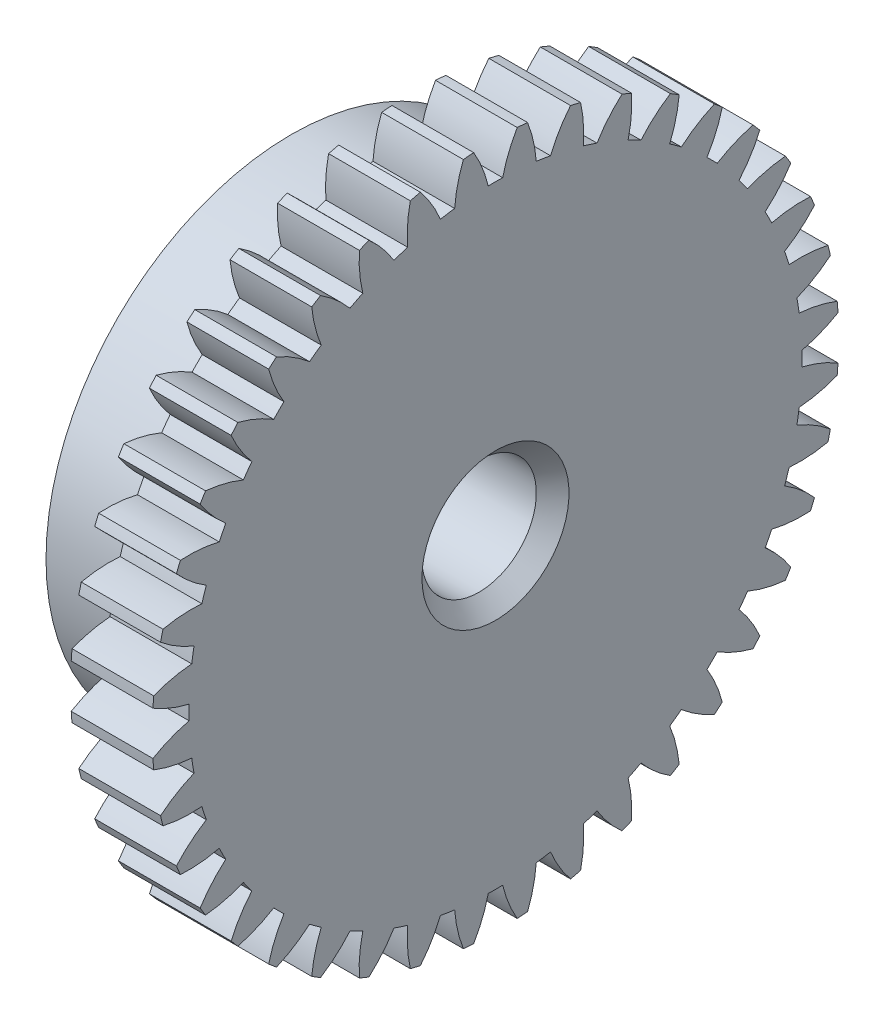
SolidWorks part; units mm, degrees
ref_plane "Plane1" through (0, 0, 0) normal (0, 0, 1) x (1, 0, 0)
ref_plane "Plane2" through (0, 0, 0) normal (0, 1, 0) x (1, 0, 0)
ref_plane "Plane3" through (0, 0, 0) normal (1, 0, 0) x (0, 0, -1)
sketch "HoldingSke" plane through (0, 0, 0) normal (0, 1, 0) x (1, 0, 0)
  line L0 (0, 0) -> (0.383, -0.3214)
  line L1 (-15, 0) -> (100, 0) construction
  line L2 (0, 0) -> (-2.1039, 2.3779)
  line L3 (0, 0) -> (-11.863, 4.5341)
  line L4 (0, 0) -> (6.6156, 5.5511)
  line L5 (0, 0) -> (-23.4238, -8.7364)
  line L6 (0, 0) -> (-8.2896, -5.593)
  line L7 (-2.1039, 2.3779) -> (3.2774, 26.7919)
  line L8 (-76.2, 54.61) -> (-73.9, 54.61)
  line L9 (-71.009, 38.7566) -> (-53.1078, 45.2721)
  line L10 (-76.2, 71.12) -> (104.1128, 71.12)
  line L11 (0, 0) -> (-10, 0)
  line L12 (-76.2, 101.6) -> (-76.133, 101.6)
  line L13 (24.9733, 27.94) -> (52.9518, 28.4284)
  line L14 (24.9733, 27.94) -> (24.9743, 27.94)
  line L15 (24.9733, 27.94) -> (100.4006, 29.5858)
  line L16 (-63.627, -2) -> (-12.827, -2)
  circle A0 centre (0, 0) radius 7
  circle A1 centre (0, 0) radius 30
  circle A2 centre (0, 0) radius 30
  circle A3 centre (0, 0) radius 7
  dimension "MHD" = 60
  dimension "Hub_dia" = 60
  dimension "Bore" = 14
  dimension "MBD" = 14
  dimension "Num_teeth" = 40
  dimension "Pitch" = 0.5
  dimension "Overall_len" = 25
  dimension "Show_teeth" = 40
  dimension "Thickness" = 10
  dimension "OAL" = 25.0001
  dimension "T_dim" = 2.3
  dimension "Ap" = 20
  dimension "H" = 19.05
  dimension "Pitch_radius" = 180.3128
  dimension "Width" = 10
  dimension "Backlash" = 0.067
  dimension "Addendum_fac" = 1
  dimension "Dedendum_fac" = 1.25
  dimension "Clearance_fac" = 0.25
  dimension "Dedendum_add" = 0.001
  dimension "Module" = 2
sketch "BasProSke" plane through (0, 0, 0) normal (0, 1, 0) x (1, 0, 0)
  line L0 (-10, 0) -> (60, 0) construction
  line L1 (0, 0) -> (0, 42)
  line L2 (0, 0) -> (10, 0)
  line L3 (10, 0) -> (10, 42)
  line L4 (10, 42) -> (0, 42)
  dimension "Thickness" = 10
  dimension "Diameter" = 84
revolve "Base-Revolve" add sketch "BasProSke" angle 360 about L0
sketch "TooCutSke" plane through (0, 0, 0) normal (1, 0, 0) x (0, 0, -1)
  line L1 (0, 0) -> (0, 107) construction
  line L2 (0, 0) -> (-1.6876, 39.9644) construction
  line L3 (0, 0) -> (-6.2726, 79.7007) construction
  line L4 (-1.6876, 39.9644) -> (-3.1363, 39.8504) construction
  arc A0 (0.8828, 37.4886) -> (-0.8828, 37.4886) centre (0, 0) ccw
  arc A1 (2.6784, 41.94) -> (-2.6784, 41.94) centre (0, 0) ccw
  circle A2 centre (0, 0) radius 40 construction
  circle A3 centre (0, 0) radius 37.5877 construction
  arc A4 (-0.8828, 37.4886) -> (-2.6784, 41.94) centre (-16.451, 33.7965) ccw
  arc A5 (2.6784, 41.94) -> (0.8828, 37.4886) centre (16.451, 33.7965) ccw
  dimension "Root_dia" = 74.998
  dimension "Overcut_dia" = 84.0508
  dimension "Pitch_dia" = 80
  dimension "Base_dia" = 75.1754
  dimension "Flank_rad" = 16
  dimension "Half_ang" = 4.5
  dimension "Half_CT" = 1.4531
extrude "ToothCut" cut sketch "TooCutSke" along normal through all
fillet "Breaks" [suppressed] radius 0.04
fillet "RootFillets" [suppressed] radius 0.501
pattern_circular "TeethCuts" count 40 every 9 about axis through (-10, 0, 0) along (1, 0, 0) of "ToothCut", "RootFillets", "Breaks"
sketch "HubNeaOneSke" plane through (0, 0, 0) normal (-1, 0, 0) x (0, 0, 1)
  circle A0 centre (0, 0) radius 30
  dimension "Diameter" = 60
extrude "HubNearOne" add sketch "HubNeaOneSke" along normal blind 15.0001
sketch "HubNeaBotSke" plane through (0, 0, 0) normal (-1, 0, 0) x (0, 0, 1)
  circle A0 centre (0, 0) radius 30
  dimension "Diameter" = 60
extrude "HubNearBoth" [suppressed] add sketch "HubNeaBotSke" along normal blind 7.5
ref_plane "FarPln" through (10, 0, 0) normal (1, 0, 0) x (0, 0, -1)
sketch "HubFarSke" plane through (10, 0, 0) normal (1, 0, 0) x (0, 0, -1)
  circle A0 centre (0, 0) radius 30
  dimension "Diameter" = 60
extrude "HubFar" [suppressed] add sketch "HubFarSke" along normal blind 7.5
sketch "BorSke" plane through (0, 0, 0) normal (1, 0, 0) x (0, 0, -1)
  circle A0 centre (0, 0) radius 7
  dimension "Diameter" = 14
extrude "Bore" cut sketch "BorSke" along normal mid plane 50.0001
sketch "KeySke" plane through (0, 0, 0) normal (1, 0, 0) x (0, 0, -1)
  line L0 (-2.5, 0) -> (-2.5, 9.3)
  line L1 (-2.5, 9.3) -> (2.5, 9.3)
  line L2 (2.5, 9.3) -> (2.5, 0)
  line L3 (0, 0) -> (0, 34) construction
  line L4 (-2.5, 0) -> (2.5, 0)
  dimension "Offset" = 9.3
  dimension "Width" = 5
extrude "Keyway" [suppressed] cut sketch "KeySke" along normal mid plane 50.0001
pattern_circular "Keyway2" [suppressed] count 2 every 90 about axis through (-10, 0, 0) along (1, 0, 0)
chamfer "倒角1" distance 2 angle 45 2 edges at (10, 0, 7) (-15.0001, 0, 7)
equation "' \"Module@HoldingSke\" = 6.35"
equation "' \"Num_teeth@HoldingSke\" = 12"
equation "' \"Ap@HoldingSke\" =  20"
equation "' \"Ap@HoldingSke\" = 20"
equation "' \"Width@HoldingSke\" = 0.5 * 25.4"
equation "' \"Hub_dia@HoldingSke\"= 1 * 25.4"
equation "' \"Hub_dia@HoldingSke\" = 1 * 25.4"
equation "' \"Overall_len@HoldingSke\" = 1.0 * 25.4"
equation "' \"Bore@HoldingSke\" = 0.75 * 25.4"
equation "' \"T_dim@HoldingSke\" = 0.1 * 25.4"
equation "' \"Width@KeySke\" = 0.25 * 25.4"
equation "' \"Show_teeth@HoldingSke\" = 13"
equation "' \"Backlash@HoldingSke\" = 0.009 * 25.4"
equation "' \"Addendum_fac@HoldingSke\" = 1.0"
equation "' \"Dedendum_fac@HoldingSke\" = 1.25"
equation "' \"Dedendum_add@HoldingSke\" = 0.00005 * 25.4"
equation "' \"Clearance_fac@HoldingSke\" = 0.25"
equation "\"Pitch@HoldingSke\" = 1 / \"Module@HoldingSke\""
equation "\"Overcut_dia@TooCutSke\" = (\"Num_teeth@HoldingSke\" + 2 * \"Addendum_fac@HoldingSke\") / \"Pitch@HoldingSke\" + 0.002 * 25.4"
equation "\"Pitch_dia@TooCutSke\" = \"Num_teeth@HoldingSke\" / \"Pitch@HoldingSke\""
equation "\"Base_dia@TooCutSke\" = \"Num_teeth@HoldingSke\" / \"Pitch@HoldingSke\" * cos((\"Ap@HoldingSke\"  * 3.14159265 / 180))"
equation "\"Root_dia@TooCutSke\" = (\"Num_teeth@HoldingSke\" + 2) / \"Pitch@HoldingSke\" - 2 * (\"Addendum_fac@HoldingSke\" + \"Dedendum_fac@HoldingSke\") / \"Pitch@HoldingSke\" - \"Dedendum_add@HoldingSke\" * 2"
equation "\"Half_ang@TooCutSke\" = 180 / \"Num_teeth@HoldingSke\""
equation "\"Half_CT@TooCutSke\" = \"Num_teeth@HoldingSke\" / \"Pitch@HoldingSke\" * sin((3.14159265 / 2 / \"Num_teeth@HoldingSke\")) / 2 - 7 * \"Backlash@HoldingSke\" / 4"
equation "\"Flank_rad@TooCutSke\" = \"Num_teeth@HoldingSke\" / \"Pitch@HoldingSke\" / 5"
equation "\"Radius@RootFillets\" = \"Clearance_fac@HoldingSke\" / \"Pitch@HoldingSke\" + \"Dedendum_add@HoldingSke\""
equation "\"Break_rad@Breaks\" = 0.02 / \"Pitch@HoldingSke\""
equation "\"Thickness@HoldingSke\" = \"Width@HoldingSke\""
equation "\"OAL@HoldingSke\" = \"Thickness@HoldingSke\""
equation "\"MHD@HoldingSke\" = (\"Num_teeth@HoldingSke\" + 2) / \"Pitch@HoldingSke\" - 2 * (\"Addendum_fac@HoldingSke\" + \"Dedendum_fac@HoldingSke\")  / \"Pitch@HoldingSke\" - \"Dedendum_add@HoldingSke\" * 2"
equation "\"MBD@HoldingSke\" = (\"Num_teeth@HoldingSke\" + 2) / \"Pitch@HoldingSke\" - 2 * (\"Addendum_fac@HoldingSke\" + \"Dedendum_fac@HoldingSke\")  / \"Pitch@HoldingSke\" - \"Dedendum_add@HoldingSke\" * 2 - 0.002 * 25.4"
equation "\"MHD@HoldingSke\" = ((sgn( \"MHD@HoldingSke\" - \"Hub_dia@HoldingSke\" )-1)*( \"MHD@HoldingSke\" - \"Hub_dia@HoldingSke\" ))/-2+ \"Hub_dia@HoldingSke\""
equation "\"MBD@HoldingSke\" = ((sgn( \"MBD@HoldingSke\" - \"Bore@HoldingSke\" )-1)*( \"MBD@HoldingSke\" - \"Bore@HoldingSke\" ))/-2+ \"Bore@HoldingSke\""
equation "\"OAL@HoldingSke\" = ((sgn( \"OAL@HoldingSke\" - \"Overall_len@HoldingSke\" )+1)*( \"OAL@HoldingSke\" - \"Overall_len@HoldingSke\" ))/2 + \"Overall_len@HoldingSke\" + 0.000002 * 25.4"
equation "\"Num_teeth@TeethCuts\" = int( \"Show_teeth@HoldingSke\" ) + 1"
equation "\"Num_teeth@TeethCuts\" = ((sgn( \"Num_teeth@TeethCuts\" - \"Num_teeth@HoldingSke\" )-1)*( \"Num_teeth@TeethCuts\" - \"Num_teeth@HoldingSke\" ))/-2+ \"Num_teeth@HoldingSke\""
equation "\"Num_teeth@TeethCuts\" = ((sgn( \"Num_teeth@TeethCuts\" - 2.0)+1)*( \"Num_teeth@TeethCuts\" - 2.0))/2 +2.0"
equation "\"Angle@TeethCuts\" = 360.0 / \"Num_teeth@HoldingSke\""
equation "\"Diameter@BasProSke\" = (\"Num_teeth@HoldingSke\" + 2 * \"Addendum_fac@HoldingSke\") / \"Pitch@HoldingSke\""
equation "\"Thickness@BasProSke\"  = \"Thickness@HoldingSke\""
equation "' \"Fillet_rad@BasProSke\" =  \"Thickness@HoldingSke\" * 0.05"
equation "' \"Fillet_rad@BasProSke\" = \"Thickness@HoldingSke\" * 0.05"
equation "\"MHD@HoldingSke\" = ((sgn( \"MHD@HoldingSke\" - \"Root_dia@TooCutSke\" )-1)*( \"MHD@HoldingSke\" - \"Root_dia@TooCutSke\" ))/-2+ \"Root_dia@TooCutSke\""
equation "\"Diameter@HubNeaOneSke\" = \"MHD@HoldingSke\""
equation "\"Length@HubNearOne\" = \"OAL@HoldingSke\" - \"Thickness@BasProSke\""
equation "\"Diameter@HubNeaBotSke\" = \"MHD@HoldingSke\""
equation "\"Length@HubNearBoth\" = ( \"OAL@HoldingSke\" - \"Thickness@BasProSke\" ) / 2.0"
equation "\"Thickness@FarPln\" = \"Thickness@BasProSke\""
equation "\"Diameter@HubFarSke\" = \"MHD@HoldingSke\""
equation "\"Length@HubFar\" = ( \"OAL@HoldingSke\" - \"Thickness@BasProSke\" ) / 2.0"
equation "\"Diameter@BorSke\" = \"MBD@HoldingSke\""
equation "\"D1@Bore\" = \"OAL@HoldingSke\" * 2.0"
equation "\"D1@Keyway\" = \"OAL@HoldingSke\" * 2.0"
equation "\"Offset@KeySke\" = \"T_dim@HoldingSke\" + \"MBD@HoldingSke\" / 2.0"
